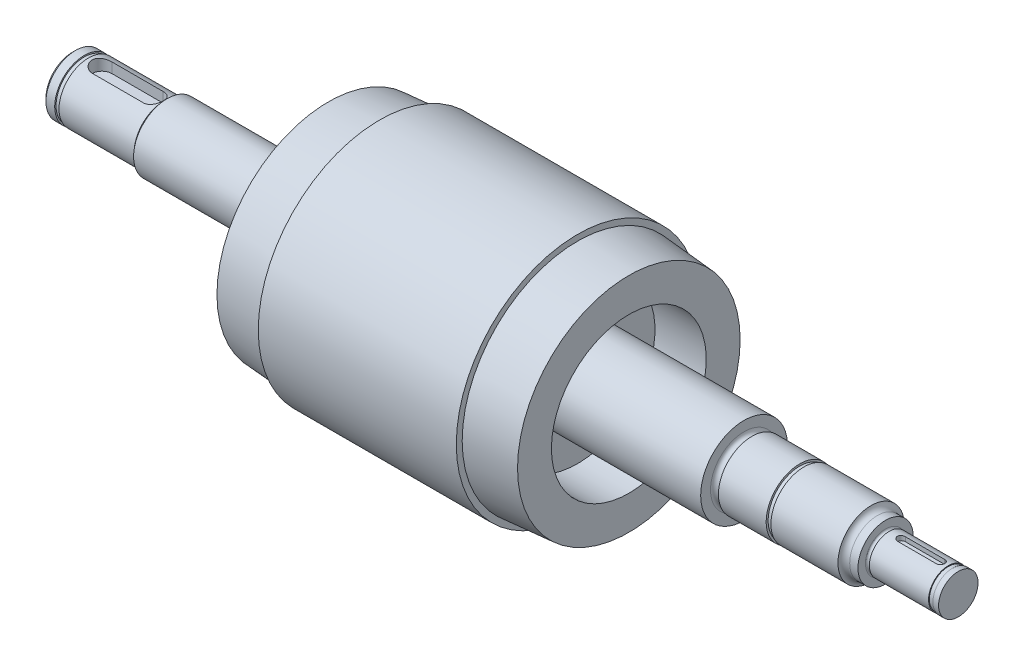
SolidWorks part; units mm, degrees
ref_plane "Plan de face" through (0, 0, 0) normal (0, 0, 1) x (1, 0, 0)
ref_plane "Plan de dessus" through (0, 0, 0) normal (0, 1, 0) x (1, 0, 0)
ref_plane "Plan de droite" through (0, 0, 0) normal (1, 0, 0) x (0, 0, -1)
sketch "Esquisse1" plane through (0, 0, 0) normal (0, 0, 1) x (1, 0, 0)
  line L0 (-12.6282, 0) -> (240.7243, 0) construction
  line L1 (3, 7.5) -> (0.8, 7.5)
  line L2 (64.86, 28.22) -> (77.86, 29.25)
  line L3 (0, 0) -> (0, 6.7)
  line L4 (24, 7.5) -> (24, 8.5)
  line L5 (224.59, 0) -> (224.59, 5)
  line L6 (24, 8.5) -> (54.614, 8.5)
  line L7 (55.48, 8.5) -> (55.48, 11)
  line L8 (55.48, 11) -> (77.86, 11)
  line L9 (77.86, 11) -> (77.86, 19.63)
  line L10 (77.86, 19.63) -> (64.86, 19.63)
  line L11 (64.86, 19.63) -> (64.86, 28.22)
  line L12 (77.86, 29.25) -> (77.86, 30.745)
  line L13 (77.86, 30.745) -> (128.06, 30.745)
  line L14 (204.0562, 7) -> (206.15, 7)
  line L15 (128.06, 29.25) -> (128.06, 30.745)
  line L16 (141.06, 19.63) -> (141.06, 28.22)
  line L17 (128.06, 19.63) -> (141.06, 19.63)
  line L18 (128.06, 11) -> (128.06, 19.63)
  line L19 (170.27, 11) -> (128.06, 11)
  line L20 (170.27, 8.5) -> (170.27, 11)
  line L21 (184.37, 8.5) -> (172.27, 8.5)
  line L22 (206.15, 7) -> (206.15, 5.0943)
  line L23 (223.15, 5) -> (224.59, 5)
  line L24 (141.06, 28.22) -> (128.06, 29.25)
  line L25 (202.47, 8.39) -> (185.47, 8.39)
  line L26 (184.37, 8.5) -> (184.37, 8)
  line L27 (184.37, 8) -> (185.47, 8)
  line L28 (185.47, 8.39) -> (185.47, 8)
  line L29 (222.05, 5) -> (207.04, 5)
  line L30 (0, 0) -> (224.59, 0)
  line L31 (222.05, 5) -> (222.05, 4.8)
  line L32 (222.05, 4.8) -> (223.15, 4.8)
  line L33 (223.15, 5) -> (223.15, 4.8)
  line L34 (0, 6.7) -> (0.8, 7.5)
  line L35 (4.1, 7.5) -> (23.134, 7.5)
  line L37 (3, 7.5) -> (3, 7.15)
  line L38 (3, 7.15) -> (4.1, 7.15)
  line L39 (4.1, 7.5) -> (4.1, 7.15)
  arc A0 (24, 7.5) -> (23.134, 7.5) centre (23.567, 7.75) cw
  arc A1 (55.48, 8.5) -> (54.614, 8.5) centre (55.047, 8.75) cw
  arc A2 (170.27, 8.5) -> (172.27, 8.5) centre (171.27, 8.5) ccw
  arc A3 (204.0562, 7) -> (202.47, 8.39) centre (204.0562, 8.6) cw
  arc A4 (206.15, 5.0943) -> (207.04, 5) centre (206.6, 5.0943) ccw
  point P5 (0, 7.5)
  point P52 (-23.5782, -52.8256)
  dimension "D5" = 0.5
  dimension "D8" = 0.5
  dimension "D28" = 1.6
  dimension "D31" = 0.9
  dimension "D39" = 1
  dimension "D1" = 0.8
  dimension "D3" = 24
  dimension "D4" = 15
  dimension "D6" = 0.25
  dimension "D7" = 17
  dimension "D9" = 31.48
  dimension "D10" = 22
  dimension "D11" = 22.38
  dimension "D12" = 39.26
  dimension "D13" = 13
  dimension "D14" = 56.44
  dimension "D15" = 58.5
  dimension "D16" = 39.26
  dimension "D17" = 42.21
  dimension "D18" = 61.49
  dimension "D19" = 22
  dimension "D20" = 15.9
  dimension "D21" = 17
  dimension "D22" = 14.1
  dimension "D23" = 16.78
  dimension "D24" = 1.1
  dimension "D25" = 16
  dimension "D26" = 17
  dimension "D27" = 14
  dimension "D29" = 3.68
  dimension "D30" = 10
  dimension "D32" = 9.6
  dimension "D33" = 1.1
  dimension "D34" = 1.44
  dimension "D35" = 50.2
  dimension "D36" = 14.3
  dimension "D37" = 1.1
  dimension "D38" = 19.9
revolve "Révolution1" add sketch "Esquisse1" angle 360 about L0
ref_plane "Plan1" through (13.617, 7.5, 0) normal (0, 1, 0) x (0, 0, -1)
sketch "Esquisse2" plane through (13.617, 7.5, 0) normal (0, 1, 0) x (0, 0, -1)
  line L0 (2.5, 6.117) -> (2.5, -6.883)
  line L1 (-2.5, -6.883) -> (-2.5, 6.117)
  line L2 (6.7, 13.617) -> (-6.7, 13.617) construction
  line L3 (0, 14.4827) -> (0, -10.9227) construction
  arc A0 (2.5, -6.883) -> (-2.5, -6.883) centre (0, -6.883) cw
  arc A1 (-2.5, 6.117) -> (2.5, 6.117) centre (0, 6.117) cw
  dimension "D3" = 7.5
  dimension "D1" = 5
  dimension "D2" = 13
extrude "Enlèv. mat.-Extru.1" cut sketch "Esquisse2" against normal blind 3
ref_plane "Plan2" through (214.545, 5, 0) normal (0, 1, 0) x (0, 0, -1)
sketch "Esquisse3" plane through (214.545, 5, 0) normal (0, 1, 0) x (0, 0, -1)
  line L0 (0, -11.5022) -> (0, 9.2229) construction
  line L1 (1, 4.395) -> (1, -5.605)
  line L2 (-1, -5.605) -> (-1, 4.395)
  line L3 (-7, 8.395) -> (7, 8.395) construction
  arc A0 (1, -5.605) -> (-1, -5.605) centre (0, -5.605) cw
  arc A1 (-1, 4.395) -> (1, 4.395) centre (0, 4.395) cw
  dimension "D1" = 2
  dimension "D2" = 10
  dimension "D3" = 4
extrude "Enlèv. mat.-Extru.2" cut sketch "Esquisse3" against normal blind 1.2
